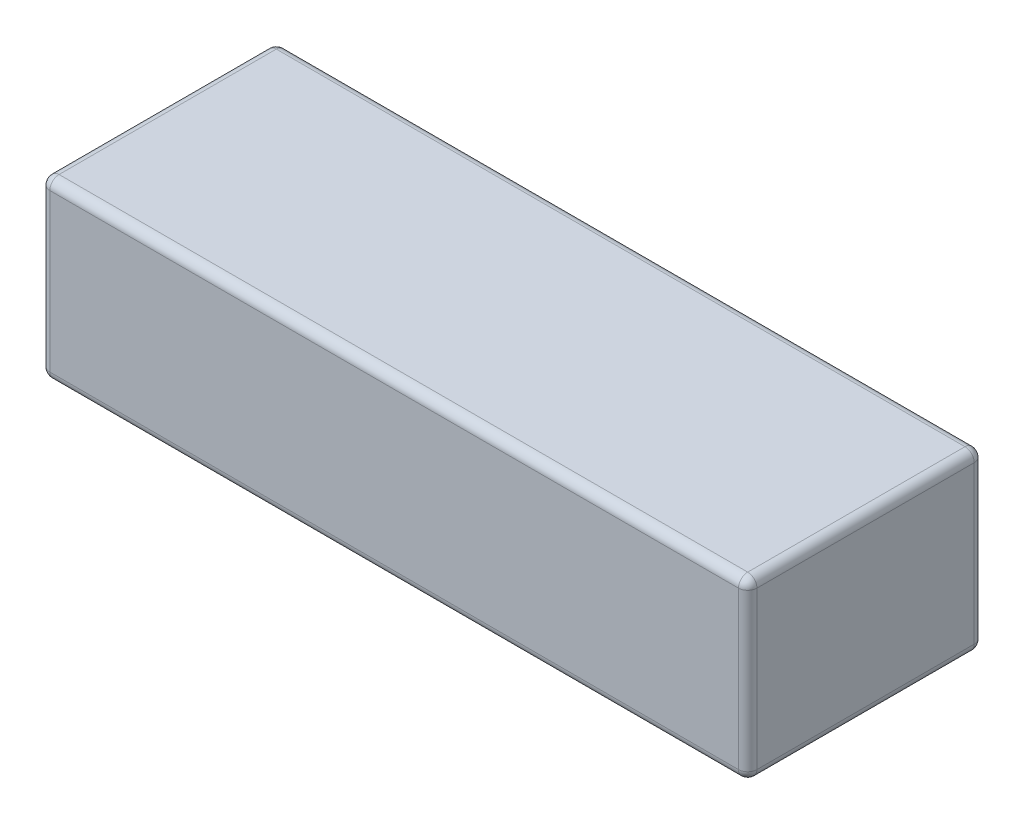
SolidWorks part; units mm, degrees
material "Magnezyum Alaşımı"
ref_plane "Ön Düzlem" through (0, 0, 0) normal (0, 0, 1) x (1, 0, 0)
ref_plane "Üst Düzlem" through (0, 0, 0) normal (0, 1, 0) x (1, 0, 0)
ref_plane "Sağ Düzlem" through (0, 0, 0) normal (1, 0, 0) x (0, 0, -1)
sketch "Çizim1" plane through (0, 0, 0) normal (0, 0, 1) x (1, 0, 0)
  line L1 (0, 0) -> (153, 0)
  line L2 (0, 0) -> (0, 38)
  line L3 (0, 38) -> (153, 38)
  line L4 (153, 0) -> (153, 38)
  dimension "D1" = 153
  dimension "D2" = 38
extrude "Yükseklik-Ekstrüzyon1" add sketch "Çizim1" along normal blind 51
fillet "Radyus1" radius 2 12 edges at (0, 19, 0) (0, 0, 25.5) (76.5, 0, 0) (153, 0, 25.5) (153, 19, 0) (153, 19, 51) (76.5, 0, 51) (0, 19, 51) (153, 38, 25.5) (76.5, 38, 51) (0, 38, 25.5) (76.5, 38, 0)
sketch "Çizim3" plane through (0, 0, 51) normal (0, 0, 1) x (1, 0, 0)
  text T0 "Profuse\r\n14,8V Lipo Batarya 6200mAh 40C - 4s Lipo Pil"
